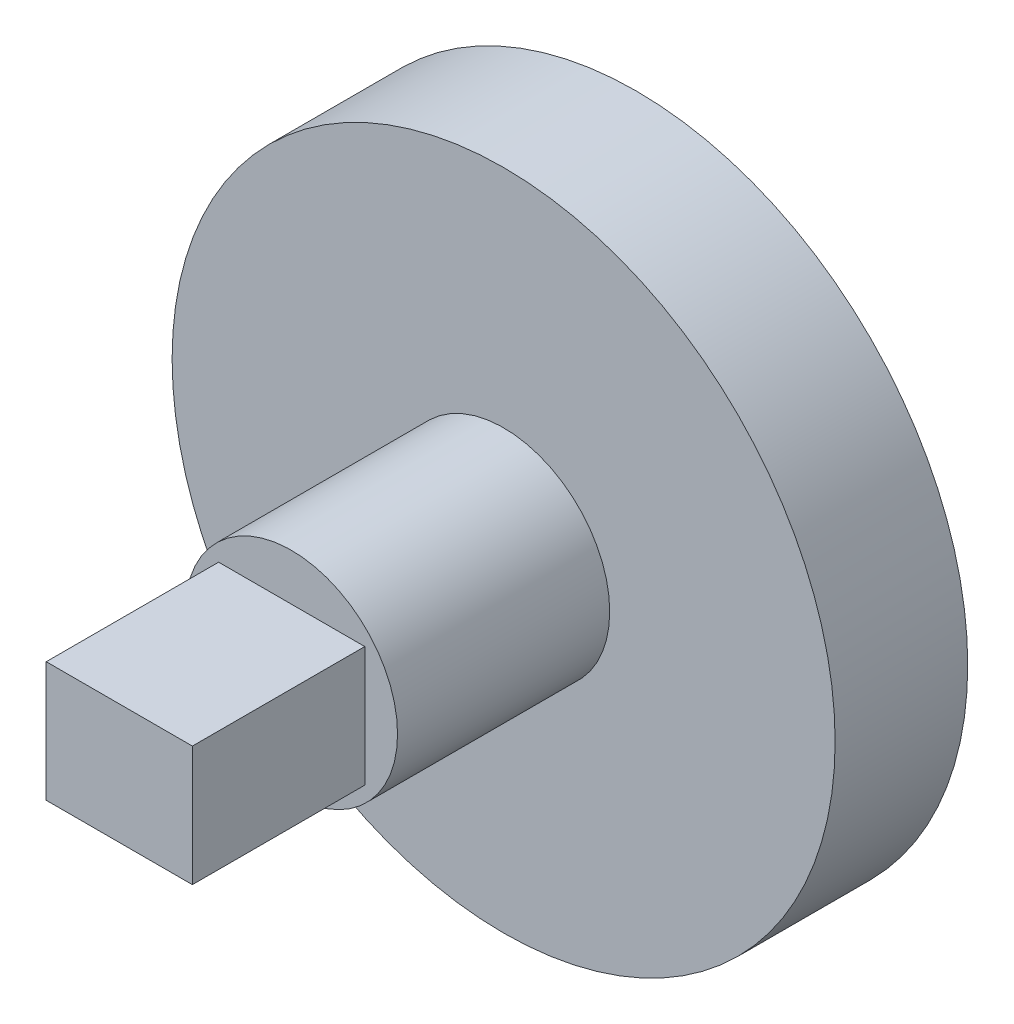
SolidWorks part; units mm, degrees
ref_plane "Front Plane" through (0, 0, 0) normal (0, 0, 1) x (1, 0, 0)
ref_plane "Top Plane" through (0, 0, 0) normal (0, 1, 0) x (1, 0, 0)
ref_plane "Right Plane" through (0, 0, 0) normal (1, 0, 0) x (0, 0, -1)
sketch "Sketch1" plane through (0, 0, 0) normal (0, 0, 1) x (1, 0, 0)
  line L0 (12.5, 0) -> (-12.5, 0) construction
  circle A0 centre (0, 0) radius 12.5
extrude "Boss-Extrude1" add sketch "Sketch1" along normal blind 5
sketch "Sketch2" plane through (0, 0, 5) normal (0, 0, 1) x (1, 0, 0)
  circle A0 centre (0, 0) radius 4
extrude "Boss-Extrude2" add sketch "Sketch2" along normal blind 8
sketch "Sketch3" plane through (0, 0, 13) normal (0, 0, 1) x (1, 0, 0)
  line L0 (-2.7457, 2.2387) -> (2.7643, 2.2387)
  line L1 (-2.7457, 2.2387) -> (-2.7457, -2.2873)
  line L2 (-2.7457, -2.2873) -> (2.7643, -2.2873)
  line L3 (2.7643, 2.2387) -> (2.7643, -2.2873)
  line L4 (-2.7457, 2.2387) -> (2.7643, -2.2873) construction
  line L5 (-2.7457, -2.2873) -> (2.7643, 2.2387) construction
  point P4 (0.0093, -0.0243)
extrude "Boss-Extrude3" add sketch "Sketch3" along normal blind 6.5
